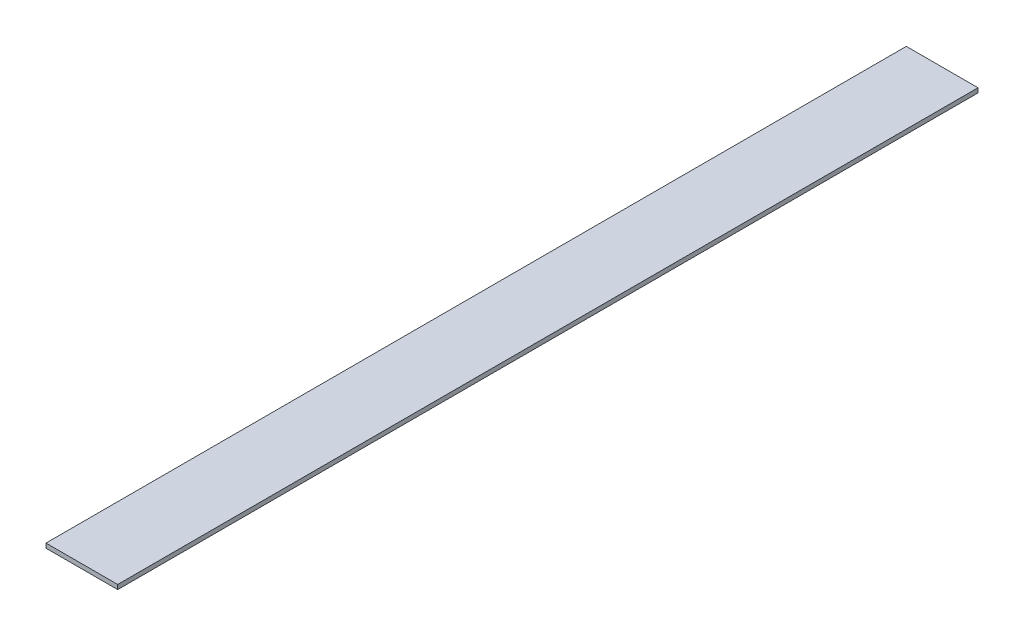
SolidWorks part; units mm, degrees
ref_plane "Front Plane" through (0, 0, 0) normal (0, 0, 1) x (1, 0, 0)
ref_plane "Top Plane" through (0, 0, 0) normal (0, 1, 0) x (1, 0, 0)
ref_plane "Right Plane" through (0, 0, 0) normal (1, 0, 0) x (0, 0, -1)
sketch "Sketch1" plane through (0, 0, 0) normal (0, 1, 0) x (1, 0, 0)
  line L1 (-12.7, -152.4) -> (12.7, -152.4)
  line L2 (-12.7, -152.4) -> (-12.7, 152.4)
  line L3 (-12.7, 152.4) -> (12.7, 152.4)
  line L4 (12.7, -152.4) -> (12.7, 152.4)
  line L5 (-12.7, -152.4) -> (12.7, 152.4) construction
  line L6 (-12.7, 152.4) -> (12.7, -152.4) construction
  point P0 (0, 0)
  dimension "D1" = 304.8
  dimension "D2" = 25.4
extrude "Boss-Extrude1" add sketch "Sketch1" along normal blind 1.5875
